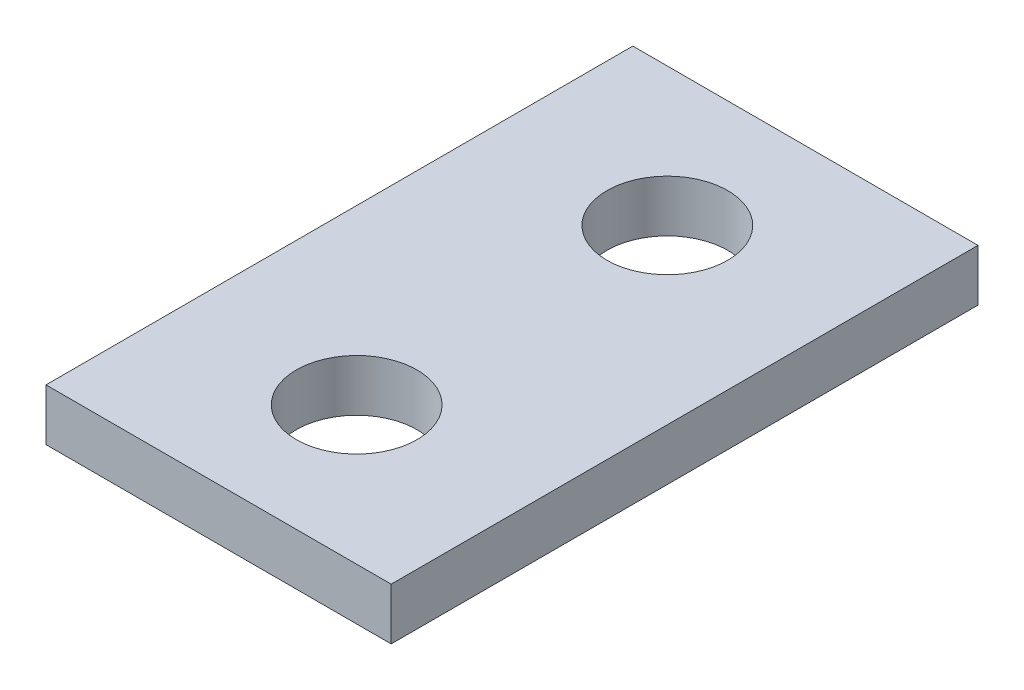
SolidWorks part; units mm, degrees
ref_plane "Front Plane" through (0, 0, 0) normal (0, 0, 1) x (1, 0, 0)
ref_plane "Top Plane" through (0, 0, 0) normal (0, 1, 0) x (1, 0, 0)
ref_plane "Right Plane" through (0, 0, 0) normal (1, 0, 0) x (0, 0, -1)
sketch "Sketch1" plane through (0, 0, 0) normal (0, 1, 0) x (1, 0, 0)
  line L0 (0, -17) -> (0, 17) construction
  line L1 (-10, 17) -> (10, 17)
  line L2 (-10, 17) -> (-10, -17)
  line L3 (-10, -17) -> (10, -17)
  line L4 (10, 17) -> (10, -17)
  line L5 (-10, 17) -> (10, -17) construction
  line L6 (-10, -17) -> (10, 17) construction
  circle A0 centre (0, -9) radius 3.5
  circle A1 centre (0, 9) radius 3.5
  point P0 (0, 0)
  point P12 (0, 0)
  dimension "D3" = 7
  dimension "D4" = 9
  dimension "D1" = 34
  dimension "D2" = 20
  dimension "D5" = 9
extrude "Boss-Extrude1" add sketch "Sketch1" along normal blind 3
